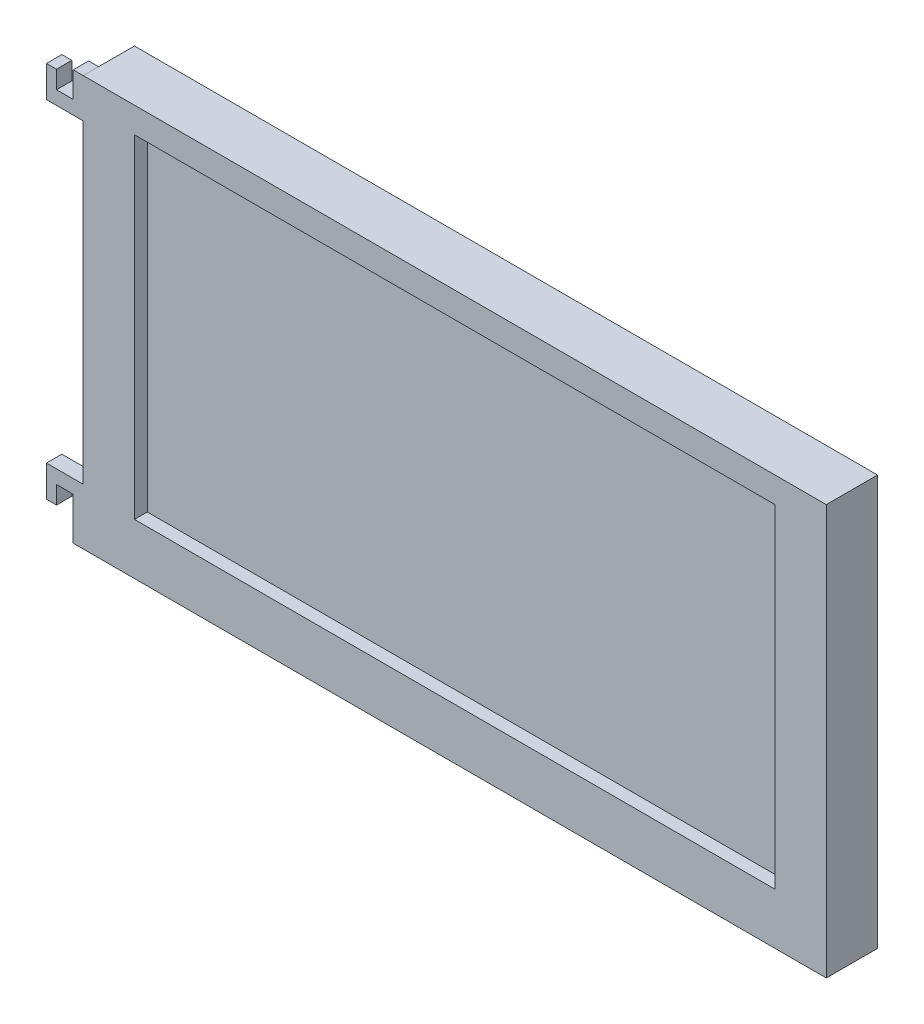
SolidWorks part; units mm, degrees
material "2024 Alloy"
ref_plane "Front Plane" through (0, 0, 0) normal (0, 0, 1) x (1, 0, 0)
ref_plane "Top Plane" through (0, 0, 0) normal (0, 1, 0) x (1, 0, 0)
ref_plane "Right Plane" through (0, 0, 0) normal (1, 0, 0) x (0, 0, -1)
sketch "Sketch1" plane through (0, 0, 0) normal (0, 0, 1) x (1, 0, 0)
  line L1 (-184.15, 101.6) -> (184.15, 101.6)
  line L2 (-184.15, 101.6) -> (-184.15, -101.6)
  line L3 (-184.15, -101.6) -> (184.15, -101.6)
  line L4 (184.15, 101.6) -> (184.15, -101.6)
  point P4 (0, 101.6)
  point P6 (-184.15, 0)
  dimension "D1" = 368.3
  dimension "D2" = 203.2
extrude "Boss-Extrude1" add sketch "Sketch1" along normal mid plane 25.4
sketch "Sketch2" plane through (0, 0, 12.7) normal (0, 0, 1) x (1, 0, 0)
  line L0 (-184.15, 101.6) -> (-184.15, -101.6) construction
  line L1 (-158.75, 88.9) -> (158.75, 88.9)
  line L2 (-158.75, 88.9) -> (-158.75, -76.2)
  line L3 (-158.75, -76.2) -> (158.75, -76.2)
  line L4 (158.75, 88.9) -> (158.75, -76.2)
  line L5 (184.15, 101.6) -> (-184.15, 101.6) construction
  line L6 (-184.15, -101.6) -> (184.15, -101.6) construction
  point P6 (0, 88.9)
  dimension "D1" = 25.4
  dimension "D2" = 12.7
  dimension "D3" = 25.4
extrude "Cut-Extrude1" cut sketch "Sketch2" against normal blind 6.35
sketch "Sketch4" plane through (0, 0, 12.7) normal (0, 0, 1) x (1, 0, 0)
  line L0 (184.15, -101.6) -> (184.15, 101.6) construction
  line L1 (184.15, -101.6) -> (189.1197, -101.6)
  line L2 (184.15, -101.6) -> (184.15, -73.8207)
  line L4 (189.1197, -101.6) -> (189.1197, -80.5602)
  line L5 (184.15, -73.8207) -> (202.3622, -73.8207)
  line L7 (189.1197, -80.5602) -> (197.3925, -80.5602)
  line L8 (202.3622, -73.8207) -> (202.3622, -89.3699)
  line L11 (202.3622, -89.3699) -> (197.3925, -89.3699)
  line L12 (197.3925, -80.5602) -> (197.3925, -89.3699)
  line L13 (189.1197, 88.9) -> (197.3925, 88.9)
  line L14 (184.15, 88.0126) -> (184.15, 82.1604)
  line L15 (184.15, 82.1604) -> (202.3622, 82.1604)
  line L19 (197.3925, 88.9) -> (197.3925, 97.7097)
  line L20 (197.3925, 97.7097) -> (202.3622, 97.7097)
  line L21 (202.3622, 82.1604) -> (202.3622, 97.7097)
  line L23 (184.15, 88.0126) -> (184.15, 101.5849)
  line L24 (184.15, 101.5849) -> (189.1197, 101.5849)
  line L25 (189.1197, 88.9) -> (189.1197, 101.5849)
  line L26 (184.15, 101.6) -> (-188.2833, 101.6) construction
  dimension "D1" = 12.7
extrude "Boss-Extrude3" add sketch "Sketch4" against normal blind 7.62
mirror "Mirror2" about plane through (0, 0, 0) normal (1, 0, 0) of "Boss-Extrude3"
sketch "Sketch5" plane through (0, 0, 12.7) normal (0, 0, 1) x (1, 0, 0)
  line L1 (184.15, -73.8207) -> (215.8469, -73.8207)
  line L2 (184.15, -73.8207) -> (184.15, -136.1743)
  line L3 (184.15, -136.1743) -> (215.8469, -136.1743)
  line L4 (215.8469, -73.8207) -> (215.8469, -136.1743)
  line L5 (184.15, -73.8207) -> (225.8255, -73.8207)
  line L6 (184.15, -73.8207) -> (184.15, 105.2424)
  line L7 (184.15, 105.2424) -> (225.8255, 105.2424)
  line L8 (225.8255, -73.8207) -> (225.8255, 105.2424)
  line M20 (-189.1197, -101.6) -> (189.1197, -101.6)
  line M21 (189.1197, -101.6) -> (189.1197, -80.5602)
  line M22 (189.1197, -80.5602) -> (197.3925, -80.5602)
  line M23 (197.3925, -80.5602) -> (197.3925, -89.3699)
  line M24 (197.3925, -89.3699) -> (202.3622, -89.3699)
  line M25 (202.3622, -89.3699) -> (202.3622, -73.8207)
  line M26 (202.3622, -73.8207) -> (184.15, -73.8207)
  line M28 (184.15, 82.1604) -> (202.3622, 82.1604)
  line M29 (202.3622, 82.1604) -> (202.3622, 97.7097)
  line M30 (202.3622, 97.7097) -> (197.3925, 97.7097)
  line M31 (197.3925, 97.7097) -> (197.3925, 88.9)
  line M32 (197.3925, 88.9) -> (189.1197, 88.9)
  line M33 (189.1197, 88.9) -> (189.1197, 101.5849)
  line M34 (189.1197, 101.5849) -> (184.15, 101.5849)
extrude "Cut-Extrude2" cut sketch "Sketch5" against normal blind 20.32 contours L2 M26 M20 M21 M22 M23 M24 M25 | L6 M28 M29 M30 M31 M32 M33 M34
